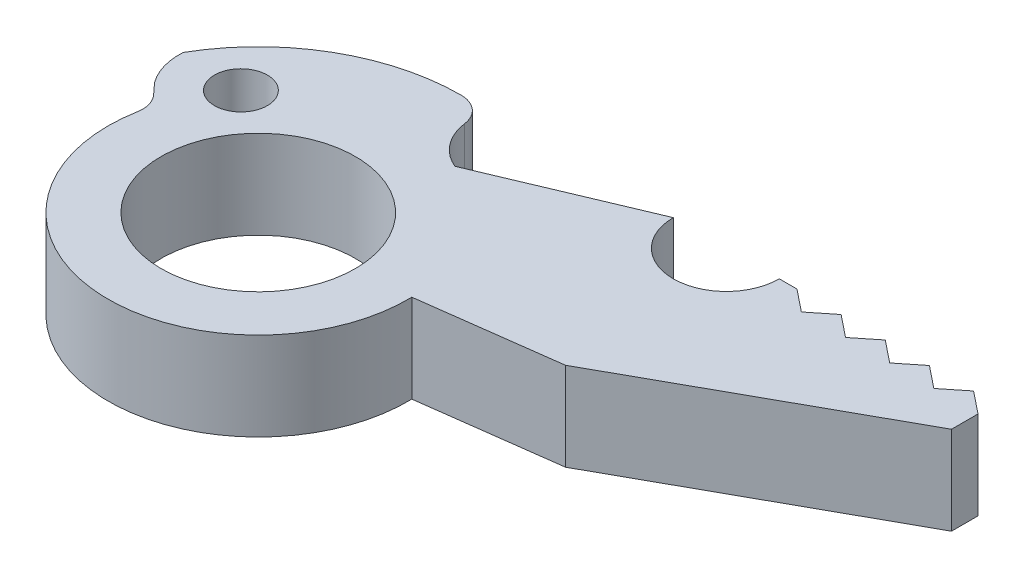
SolidWorks part; units mm, degrees
ref_plane "Front" through (0, 0, 0) normal (0, 0, 1) x (1, 0, 0)
ref_plane "Top" through (0, 0, 0) normal (0, 1, 0) x (1, 0, 0)
ref_plane "Right" through (0, 0, 0) normal (1, 0, 0) x (0, 0, -1)
sketch "Эскиз1" plane through (0, 0, 0) normal (0, 1, 0) x (1, 0, 0)
  line L0 (0, 0) -> (36.2142, 0) construction
  line L1 (0, 7) -> (36.2142, 7) construction
  line L2 (0, 11.5) -> (36.2142, 11.5) construction
  line L3 (0, 11.5) -> (0, -11.5) construction
  line L4 (0, 11.5) -> (12, 11.5)
  line L5 (18, 11.5) -> (19, 11.5)
  line L6 (19, 11.5) -> (20.25, 10.5)
  line L7 (20.25, 10.5) -> (21.5, 11.5)
  line L8 (21.5, 11.5) -> (22.75, 10.5)
  line L9 (22.75, 10.5) -> (24, 11.5)
  line L10 (24, 11.5) -> (25.25, 10.5)
  line L11 (25.25, 10.5) -> (26.5, 11.5)
  line L12 (26.5, 11.5) -> (27.75, 10.5)
  line L13 (27.75, 10.5) -> (29, 11.5)
  line L14 (29, 11.5) -> (30.25, 10.5)
  line L15 (30.25, 10.5) -> (30.25, 9)
  line L16 (30.25, 9) -> (16.187, 1.2112)
  line L17 (14, 0) -> (16.187, 1.2112) construction
  line L18 (-8.7311, 2.8071) -> (-10.485, 4.7238)
  line L19 (12, 11.5) -> (3.2964, 7.8348)
  line L20 (16.187, 1.2112) -> (7, 0)
  circle A0 centre (0, 0) radius 5.5
  circle A1 centre (0, 0) radius 7
  circle A2 centre (-6.4807, 5.5) radius 1.5
  arc A3 (0, 11.5) -> (-10.485, 4.7238) centre (0, 0) ccw
  arc A4 (1.4866, 10.2) -> (0, 11.5) centre (0, 10) ccw
  arc A5 (12, 11.5) -> (18, 11.5) centre (15, 11.5) ccw
  arc A7 (1.4866, 10.2) -> (3.2964, 7.8348) centre (4.4598, 10.6) ccw
  arc A9 (3.2964, 7.8348) -> (3.2964, -7.8348) centre (0, 0) cw
  circle A10 centre (14, 0) radius 2.5
  circle A11 centre (8.5, 0) radius 3
  arc A12 (3.2964, -7.8348) -> (-8.362, 1.5253) centre (0, 0) cw
  arc A13 (-8.362, 1.5253) -> (-8.7311, 2.8071) centre (-9.8377, 1.7945) ccw
  dimension "D1" = 11
  dimension "D2" = 14
  dimension "D3" = 3
  dimension "D4" = 23
  dimension "D5" = 3
  dimension "D6" = 3
  dimension "D7" = 6
  dimension "D13" = 5
  dimension "D16" = 8.5
  dimension "D8" = 12
  dimension "D9" = 1
  dimension "D10" = 1.5
  dimension "D11" = 1
  dimension "D12" = 10
  dimension "D14" = 5
  dimension "D15" = 3
extrude "Бобышка-Вытянуть2" add sketch "Эскиз1" along normal blind 5 contours A11 L20 A10 L16 L15 L14 L13 L12 L11 L10 L9 L8 L7 L6 L5 A5 L19 A9 | A13 A12 A9 A11 A1 A2 A7 A4 A3 L18 | L20 A11 A9 | A9 A11 A1 L20 | L20 A10 | A11 A1 A0 | A1 A11 | A1 A11 A9 L20
sketch "Эскиз2" plane through (0, 5, 0) normal (0, 1, 0) x (1, 0, 0)
  circle A0 centre (-6.4807, 5.5) radius 3.5
  arc M21 (0, 11.5) -> (-10.485, 4.7238) centre (0, 0) ccw
  line M22 (-10.485, 4.7238) -> (-8.7311, 2.8071)
  dimension "D1" = 7
extrude "Вырез-Вытянуть1" cut sketch "Эскиз2" against normal through all contours A0 M21 M22
